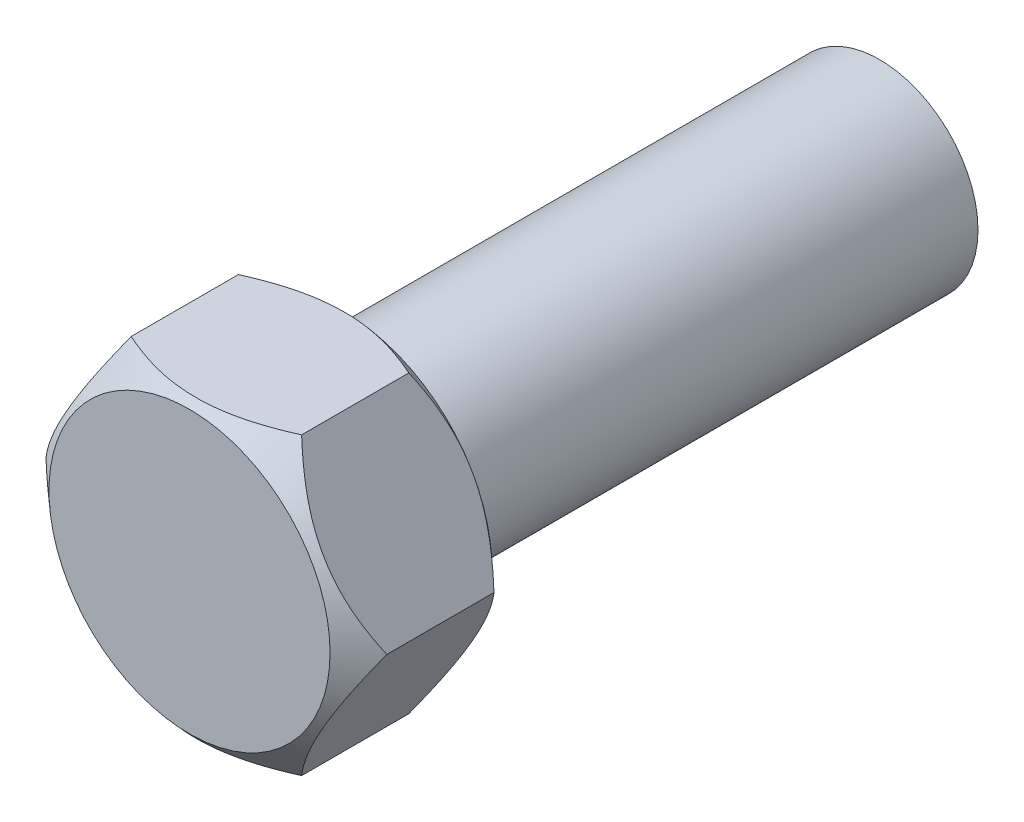
SolidWorks part; units mm, degrees
ref_plane "Alzado" through (0, 0, 0) normal (0, 0, 1) x (1, 0, 0)
ref_plane "Planta" through (0, 0, 0) normal (0, 1, 0) x (1, 0, 0)
ref_plane "Vista lateral" through (0, 0, 0) normal (1, 0, 0) x (0, 0, -1)
sketch "Croquis1" plane through (0, 0, 0) normal (0, 0, 1) x (1, 0, 0)
  circle A0 centre (0, 0) radius 7
  dimension "D1" = 14
extrude "Saliente-Extruir1" add sketch "Croquis1" along normal blind 38.1
sketch "Croquis2" plane through (0, 0, 38.1) normal (0, 0, 1) x (1, 0, 0)
  line L1 (12.1244, 0) -> (6.0622, 10.5)
  line L2 (6.0622, 10.5) -> (-6.0622, 10.5)
  line L3 (-6.0622, 10.5) -> (-12.1244, 0)
  line L4 (-12.1244, 0) -> (-6.0622, -10.5)
  line L5 (-6.0622, -10.5) -> (6.0622, -10.5)
  line L6 (6.0622, -10.5) -> (12.1244, 0)
  circle A0 centre (0, 0) radius 10.5 construction
  dimension "D1" = 21
extrude "Saliente-Extruir2" add sketch "Croquis2" along normal blind 11
sketch "Croquis3" plane through (0, 0, 49.1) normal (0, 0, 1) x (1, 0, 0)
  circle A0 centre (0, 0) radius 10
  circle A1 centre (0, 0) radius 27.5
  dimension "D1" = 55
extrude "Cortar-Extruir1" cut sketch "Croquis3" against normal blind 8 draft 48
sketch "Croquis4" plane through (0, 0, 38.1) normal (0, 0, -1) x (-1, 0, 0)
  circle A0 centre (0, 0) radius 10.5
  circle A1 centre (0, 0) radius 37.9598
extrude "Cortar-Extruir2" cut sketch "Croquis4" against normal blind 11 draft 48
